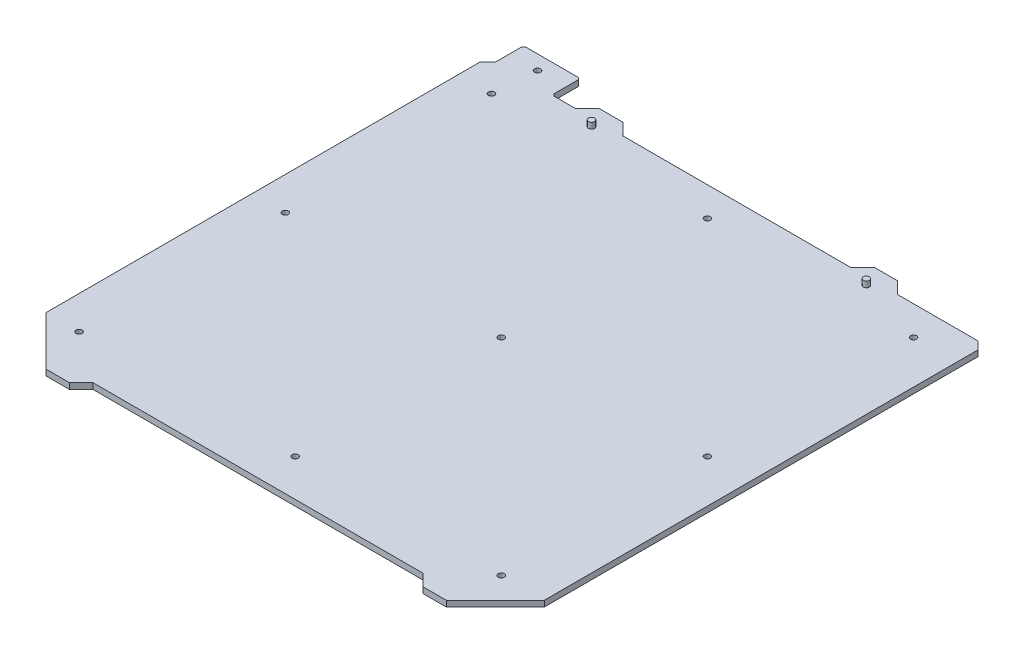
SolidWorks part; units mm, degrees
ref_plane "Front Plane" through (0, 0, 0) normal (0, 0, 1) x (1, 0, 0)
ref_plane "Top Plane" through (0, 0, 0) normal (0, 1, 0) x (1, 0, 0)
ref_plane "Right Plane" through (0, 0, 0) normal (1, 0, 0) x (0, 0, -1)
sketch "Sketch1" plane through (0, 0, 0) normal (0, 1, 0) x (1, 0, 0)
  line L0 (32.0022, 249.45) -> (32.0044, 249.45)
  line L1 (32.0044, 249.45) -> (32.0107, 249.448)
  line L2 (32.0107, 249.448) -> (32.0171, 249.447)
  line L3 (32.0171, 249.447) -> (32.019, 249.446)
  line L4 (32.019, 249.446) -> (32.0211, 249.445)
  line L5 (32.0211, 249.445) -> (32.0265, 249.442)
  line L6 (32.0265, 249.442) -> (32.0321, 249.438)
  line L7 (32.0321, 249.438) -> (32.0336, 249.437)
  line L8 (32.0336, 249.437) -> (32.0354, 249.435)
  line L9 (32.0354, 249.435) -> (33.0354, 248.435)
  line L10 (33.0354, 248.435) -> (33.0366, 248.434)
  line L11 (33.0366, 248.434) -> (33.0383, 248.432)
  line L12 (33.0383, 248.432) -> (33.0416, 248.426)
  line L13 (33.0416, 248.426) -> (33.0453, 248.421)
  line L14 (33.0453, 248.421) -> (33.0459, 248.419)
  line L15 (33.0459, 248.419) -> (33.047, 248.417)
  line L16 (33.047, 248.417) -> (33.0481, 248.411)
  line L17 (33.0481, 248.411) -> (33.0498, 248.404)
  line L18 (33.0498, 248.404) -> (33.0496, 248.402)
  line L19 (33.0496, 248.402) -> (33.05, 248.4)
  line L20 (33.05, 248.4) -> (33.05, 236.021)
  line L21 (33.05, 236.021) -> (33.9751, 235.096)
  line L22 (33.9751, 235.096) -> (34, 235.1)
  line L23 (34, 235.1) -> (45, 235.1)
  line L24 (45, 235.1) -> (45.0249, 235.096)
  line L25 (45.0249, 235.096) -> (50.9646, 241.035)
  line L26 (50.9646, 241.035) -> (50.9664, 241.037)
  line L27 (50.9664, 241.037) -> (50.9679, 241.038)
  line L28 (50.9679, 241.038) -> (50.9735, 241.042)
  line L29 (50.9735, 241.042) -> (50.9789, 241.045)
  line L30 (50.9789, 241.045) -> (50.981, 241.046)
  line L31 (50.981, 241.046) -> (50.9829, 241.047)
  line L32 (50.9829, 241.047) -> (50.9893, 241.048)
  line L33 (50.9893, 241.048) -> (50.9956, 241.05)
  line L34 (50.9956, 241.05) -> (50.9978, 241.05)
  line L35 (50.9978, 241.05) -> (51, 241.05)
  line L36 (51, 241.05) -> (63, 241.05)
  line L37 (63, 241.05) -> (63.0022, 241.05)
  line L38 (63.0022, 241.05) -> (63.0044, 241.05)
  line L39 (63.0044, 241.05) -> (63.0107, 241.048)
  line L40 (63.0107, 241.048) -> (63.0171, 241.047)
  line L41 (63.0171, 241.047) -> (63.019, 241.046)
  line L42 (63.019, 241.046) -> (63.0211, 241.045)
  line L43 (63.0211, 241.045) -> (63.0265, 241.042)
  line L44 (63.0265, 241.042) -> (63.0321, 241.038)
  line L45 (63.0321, 241.038) -> (63.0336, 241.037)
  line L46 (63.0336, 241.037) -> (63.0354, 241.035)
  line L47 (63.0354, 241.035) -> (68.9751, 235.096)
  line L48 (68.9751, 235.096) -> (69, 235.1)
  line L49 (69, 235.1) -> (185, 235.1)
  line L50 (185, 235.1) -> (185.025, 235.096)
  line L51 (185.025, 235.096) -> (190.965, 241.035)
  line L52 (190.965, 241.035) -> (190.966, 241.037)
  line L53 (190.966, 241.037) -> (190.968, 241.038)
  line L54 (190.968, 241.038) -> (190.974, 241.042)
  line L55 (190.974, 241.042) -> (190.979, 241.045)
  line L56 (190.979, 241.045) -> (190.981, 241.046)
  line L57 (190.981, 241.046) -> (190.983, 241.047)
  line L58 (190.983, 241.047) -> (190.989, 241.048)
  line L59 (190.989, 241.048) -> (190.996, 241.05)
  line L60 (190.996, 241.05) -> (190.998, 241.05)
  line L61 (190.998, 241.05) -> (191, 241.05)
  line L62 (191, 241.05) -> (203, 241.05)
  line L63 (203, 241.05) -> (203.002, 241.05)
  line L64 (203.002, 241.05) -> (203.004, 241.05)
  line L65 (203.004, 241.05) -> (203.011, 241.048)
  line L66 (203.011, 241.048) -> (203.017, 241.047)
  line L67 (203.017, 241.047) -> (203.019, 241.046)
  line L68 (203.019, 241.046) -> (203.021, 241.045)
  line L69 (203.021, 241.045) -> (203.026, 241.042)
  line L70 (203.026, 241.042) -> (203.032, 241.038)
  line L71 (203.032, 241.038) -> (203.034, 241.037)
  line L72 (203.034, 241.037) -> (203.035, 241.035)
  line L73 (203.035, 241.035) -> (208.975, 235.096)
  line L74 (208.975, 235.096) -> (209, 235.1)
  line L75 (209, 235.1) -> (250, 235.1)
  line L76 (250, 235.1) -> (250.004, 235.099)
  line L77 (250.004, 235.099) -> (250.009, 235.1)
  line L78 (250.009, 235.1) -> (250.021, 235.096)
  line L79 (250.021, 235.096) -> (250.034, 235.094)
  line L80 (250.034, 235.094) -> (250.038, 235.092)
  line L81 (250.038, 235.092) -> (250.042, 235.091)
  line L82 (250.042, 235.091) -> (250.053, 235.083)
  line L83 (250.053, 235.083) -> (250.064, 235.077)
  line L84 (250.064, 235.077) -> (250.067, 235.073)
  line L85 (250.067, 235.073) -> (250.071, 235.071)
  line L86 (250.071, 235.071) -> (254.071, 231.071)
  line L87 (254.071, 231.071) -> (254.073, 231.067)
  line L88 (254.073, 231.067) -> (254.077, 231.064)
  line L89 (254.077, 231.064) -> (254.083, 231.053)
  line L90 (254.083, 231.053) -> (254.091, 231.042)
  line L91 (254.091, 231.042) -> (254.092, 231.038)
  line L92 (254.092, 231.038) -> (254.094, 231.034)
  line L93 (254.094, 231.034) -> (254.096, 231.021)
  line L94 (254.096, 231.021) -> (254.1, 231.009)
  line L95 (254.1, 231.009) -> (254.099, 231.004)
  line L96 (254.099, 231.004) -> (254.1, 231)
  line L97 (254.1, 231) -> (254.1, 10)
  line L98 (254.1, 10) -> (254.099, 9.9957)
  line L99 (254.099, 9.9957) -> (254.1, 9.9913)
  line L100 (254.1, 9.9913) -> (254.096, 9.9787)
  line L101 (254.096, 9.9787) -> (254.094, 9.9658)
  line L102 (254.094, 9.9658) -> (254.092, 9.962)
  line L103 (254.092, 9.962) -> (254.091, 9.9577)
  line L104 (254.091, 9.9577) -> (254.083, 9.947)
  line L105 (254.083, 9.947) -> (254.077, 9.9357)
  line L106 (254.077, 9.9357) -> (254.073, 9.9329)
  line L107 (254.073, 9.9329) -> (254.071, 9.9293)
  line L108 (254.071, 9.9293) -> (229.071, -15.0707)
  line L109 (229.071, -15.0707) -> (229.067, -15.0732)
  line L110 (229.067, -15.0732) -> (229.064, -15.0766)
  line L111 (229.064, -15.0766) -> (229.053, -15.0831)
  line L112 (229.053, -15.0831) -> (229.042, -15.0906)
  line L113 (229.042, -15.0906) -> (229.038, -15.0918)
  line L114 (229.038, -15.0918) -> (229.034, -15.094)
  line L115 (229.034, -15.094) -> (229.021, -15.0962)
  line L116 (229.021, -15.0962) -> (229.009, -15.0996)
  line L117 (229.009, -15.0996) -> (229.004, -15.0992)
  line L118 (229.004, -15.0992) -> (229, -15.1)
  line L119 (229, -15.1) -> (217, -15.1)
  line L120 (217, -15.1) -> (216.996, -15.0992)
  line L121 (216.996, -15.0992) -> (216.991, -15.0996)
  line L122 (216.991, -15.0996) -> (216.979, -15.0962)
  line L123 (216.979, -15.0962) -> (216.966, -15.094)
  line L124 (216.966, -15.094) -> (216.962, -15.0918)
  line L125 (216.962, -15.0918) -> (216.958, -15.0906)
  line L126 (216.958, -15.0906) -> (216.947, -15.0831)
  line L127 (216.947, -15.0831) -> (216.936, -15.0766)
  line L128 (216.936, -15.0766) -> (216.933, -15.0732)
  line L129 (216.933, -15.0732) -> (216.929, -15.0707)
  line L130 (216.929, -15.0707) -> (210.959, -9.1)
  line L131 (210.959, -9.1) -> (43.0414, -9.1)
  line L132 (43.0414, -9.1) -> (37.0707, -15.0707)
  line L133 (37.0707, -15.0707) -> (37.0671, -15.0732)
  line L134 (37.0671, -15.0732) -> (37.0643, -15.0766)
  line L135 (37.0643, -15.0766) -> (37.053, -15.0831)
  line L136 (37.053, -15.0831) -> (37.0423, -15.0906)
  line L137 (37.0423, -15.0906) -> (37.038, -15.0918)
  line L138 (37.038, -15.0918) -> (37.0342, -15.094)
  line L139 (37.0342, -15.094) -> (37.0213, -15.0962)
  line L140 (37.0213, -15.0962) -> (37.0087, -15.0996)
  line L141 (37.0087, -15.0996) -> (37.0043, -15.0992)
  line L142 (37.0043, -15.0992) -> (37, -15.1)
  line L143 (37, -15.1) -> (25, -15.1)
  line L144 (25, -15.1) -> (24.9957, -15.0992)
  line L145 (24.9957, -15.0992) -> (24.9913, -15.0996)
  line L146 (24.9913, -15.0996) -> (24.9787, -15.0962)
  line L147 (24.9787, -15.0962) -> (24.9658, -15.094)
  line L148 (24.9658, -15.094) -> (24.962, -15.0918)
  line L149 (24.962, -15.0918) -> (24.9577, -15.0906)
  line L150 (24.9577, -15.0906) -> (24.947, -15.0831)
  line L151 (24.947, -15.0831) -> (24.9357, -15.0766)
  line L152 (24.9357, -15.0766) -> (24.9329, -15.0732)
  line L153 (24.9329, -15.0732) -> (24.9293, -15.0707)
  line L154 (24.9293, -15.0707) -> (-0.0707, 9.9293)
  line L155 (-0.0707, 9.9293) -> (-0.0732, 9.9329)
  line L156 (-0.0732, 9.9329) -> (-0.0766, 9.9357)
  line L157 (-0.0766, 9.9357) -> (-0.0831, 9.947)
  line L158 (-0.0831, 9.947) -> (-0.0906, 9.9577)
  line L159 (-0.0906, 9.9577) -> (-0.0918, 9.962)
  line L160 (-0.0918, 9.962) -> (-0.094, 9.9658)
  line L161 (-0.094, 9.9658) -> (-0.0962, 9.9787)
  line L162 (-0.0962, 9.9787) -> (-0.0996, 9.9913)
  line L163 (-0.0996, 9.9913) -> (-0.0992, 9.9957)
  line L164 (-0.0992, 9.9957) -> (-0.1, 10)
  line L165 (-0.1, 10) -> (-0.1, 231)
  line L166 (-0.1, 231) -> (-0.094, 231.034)
  line L167 (-0.094, 231.034) -> (-0.0766, 231.064)
  line L168 (-0.0766, 231.064) -> (-0.05, 231.087)
  line L169 (-0.05, 231.087) -> (-0.0174, 231.098)
  line L170 (-0.0174, 231.098) -> (0.0174, 231.098)
  line L171 (0.0174, 231.098) -> (0.025, 231.096)
  line L172 (0.025, 231.096) -> (3.95, 235.021)
  line L173 (3.95, 235.021) -> (3.95, 248.4)
  line L174 (3.95, 248.4) -> (3.9504, 248.402)
  line L175 (3.9504, 248.402) -> (3.9502, 248.404)
  line L176 (3.9502, 248.404) -> (3.9519, 248.411)
  line L177 (3.9519, 248.411) -> (3.953, 248.417)
  line L178 (3.953, 248.417) -> (3.9541, 248.419)
  line L179 (3.9541, 248.419) -> (3.9547, 248.421)
  line L180 (3.9547, 248.421) -> (3.9584, 248.426)
  line L181 (3.9584, 248.426) -> (3.9617, 248.432)
  line L182 (3.9617, 248.432) -> (3.9634, 248.434)
  line L183 (3.9634, 248.434) -> (3.9646, 248.435)
  line L184 (3.9646, 248.435) -> (4.9646, 249.435)
  line L185 (4.9646, 249.435) -> (4.9665, 249.437)
  line L186 (4.9665, 249.437) -> (4.9679, 249.438)
  line L187 (4.9679, 249.438) -> (4.9735, 249.442)
  line L188 (4.9735, 249.442) -> (4.9789, 249.445)
  line L189 (4.9789, 249.445) -> (4.981, 249.446)
  line L190 (4.981, 249.446) -> (4.9829, 249.447)
  line L191 (4.9829, 249.447) -> (4.9893, 249.448)
  line L192 (4.9893, 249.448) -> (4.9956, 249.45)
  line L193 (4.9956, 249.45) -> (4.9978, 249.45)
  line L194 (4.9978, 249.45) -> (5, 249.45)
  line L195 (5, 249.45) -> (32, 249.45)
  line L196 (32, 249.45) -> (32.0022, 249.45)
  line L197 (5.0207, 249.35) -> (4.05, 248.379)
  line L198 (4.05, 248.379) -> (4.05, 235)
  line L199 (4.05, 235) -> (4.0496, 234.998)
  line L200 (4.0496, 234.998) -> (4.0498, 234.996)
  line L201 (4.0498, 234.996) -> (4.0481, 234.989)
  line L202 (4.0481, 234.989) -> (4.047, 234.983)
  line L203 (4.047, 234.983) -> (4.0459, 234.981)
  line L204 (4.0459, 234.981) -> (4.0453, 234.979)
  line L205 (4.0453, 234.979) -> (4.0416, 234.974)
  line L206 (4.0416, 234.974) -> (4.0383, 234.968)
  line L207 (4.0383, 234.968) -> (4.0366, 234.966)
  line L208 (4.0366, 234.966) -> (4.0354, 234.965)
  line L209 (4.0354, 234.965) -> (0.0956, 231.025)
  line L210 (0.0956, 231.025) -> (0.1, 231)
  line L211 (0.1, 231) -> (0.1, 10.0414)
  line L212 (0.1, 10.0414) -> (25.0414, -14.9)
  line L213 (25.0414, -14.9) -> (36.9586, -14.9)
  line L214 (36.9586, -14.9) -> (42.9293, -8.9293)
  line L215 (42.9293, -8.9293) -> (42.9329, -8.9268)
  line L216 (42.9329, -8.9268) -> (42.9357, -8.9234)
  line L217 (42.9357, -8.9234) -> (42.947, -8.9169)
  line L218 (42.947, -8.9169) -> (42.9577, -8.9094)
  line L219 (42.9577, -8.9094) -> (42.962, -8.9082)
  line L220 (42.962, -8.9082) -> (42.9658, -8.906)
  line L221 (42.9658, -8.906) -> (42.9787, -8.9038)
  line L222 (42.9787, -8.9038) -> (42.9913, -8.9004)
  line L223 (42.9913, -8.9004) -> (42.9957, -8.9008)
  line L224 (42.9957, -8.9008) -> (43, -8.9)
  line L225 (43, -8.9) -> (211, -8.9)
  line L226 (211, -8.9) -> (211.004, -8.9008)
  line L227 (211.004, -8.9008) -> (211.009, -8.9004)
  line L228 (211.009, -8.9004) -> (211.021, -8.9038)
  line L229 (211.021, -8.9038) -> (211.034, -8.906)
  line L230 (211.034, -8.906) -> (211.038, -8.9082)
  line L231 (211.038, -8.9082) -> (211.042, -8.9094)
  line L232 (211.042, -8.9094) -> (211.053, -8.9169)
  line L233 (211.053, -8.9169) -> (211.064, -8.9234)
  line L234 (211.064, -8.9234) -> (211.067, -8.9268)
  line L235 (211.067, -8.9268) -> (211.071, -8.9293)
  line L236 (211.071, -8.9293) -> (217.041, -14.9)
  line L237 (217.041, -14.9) -> (228.959, -14.9)
  line L238 (228.959, -14.9) -> (253.9, 10.0414)
  line L239 (253.9, 10.0414) -> (253.9, 230.959)
  line L240 (253.9, 230.959) -> (249.959, 234.9)
  line L241 (249.959, 234.9) -> (209, 234.9)
  line L242 (209, 234.9) -> (208.966, 234.906)
  line L243 (208.966, 234.906) -> (208.936, 234.923)
  line L244 (208.936, 234.923) -> (208.913, 234.95)
  line L245 (208.913, 234.95) -> (208.902, 234.983)
  line L246 (208.902, 234.983) -> (208.902, 235.017)
  line L247 (208.902, 235.017) -> (208.904, 235.025)
  line L248 (208.904, 235.025) -> (202.979, 240.95)
  line L249 (202.979, 240.95) -> (191.021, 240.95)
  line L250 (191.021, 240.95) -> (185.096, 235.025)
  line L251 (185.096, 235.025) -> (185.098, 235.017)
  line L252 (185.098, 235.017) -> (185.098, 234.983)
  line L253 (185.098, 234.983) -> (185.087, 234.95)
  line L254 (185.087, 234.95) -> (185.064, 234.923)
  line L255 (185.064, 234.923) -> (185.034, 234.906)
  line L256 (185.034, 234.906) -> (185, 234.9)
  line L257 (185, 234.9) -> (69, 234.9)
  line L258 (69, 234.9) -> (68.9658, 234.906)
  line L259 (68.9658, 234.906) -> (68.9357, 234.923)
  line L260 (68.9357, 234.923) -> (68.9134, 234.95)
  line L261 (68.9134, 234.95) -> (68.9015, 234.983)
  line L262 (68.9015, 234.983) -> (68.9015, 235.017)
  line L263 (68.9015, 235.017) -> (68.9043, 235.025)
  line L264 (68.9043, 235.025) -> (62.9793, 240.95)
  line L265 (62.9793, 240.95) -> (51.0207, 240.95)
  line L266 (51.0207, 240.95) -> (45.0957, 235.025)
  line L267 (45.0957, 235.025) -> (45.0985, 235.017)
  line L268 (45.0985, 235.017) -> (45.0985, 234.983)
  line L269 (45.0985, 234.983) -> (45.0866, 234.95)
  line L270 (45.0866, 234.95) -> (45.0643, 234.923)
  line L271 (45.0643, 234.923) -> (45.0342, 234.906)
  line L272 (45.0342, 234.906) -> (45, 234.9)
  line L273 (45, 234.9) -> (34, 234.9)
  line L274 (34, 234.9) -> (33.9658, 234.906)
  line L275 (33.9658, 234.906) -> (33.9357, 234.923)
  line L276 (33.9357, 234.923) -> (33.9134, 234.95)
  line L277 (33.9134, 234.95) -> (33.9015, 234.983)
  line L278 (33.9015, 234.983) -> (33.9015, 235.017)
  line L279 (33.9015, 235.017) -> (33.9043, 235.025)
  line L280 (33.9043, 235.025) -> (32.9646, 235.965)
  line L281 (32.9646, 235.965) -> (32.9634, 235.966)
  line L282 (32.9634, 235.966) -> (32.9617, 235.968)
  line L283 (32.9617, 235.968) -> (32.9584, 235.974)
  line L284 (32.9584, 235.974) -> (32.9547, 235.979)
  line L285 (32.9547, 235.979) -> (32.9541, 235.981)
  line L286 (32.9541, 235.981) -> (32.953, 235.983)
  line L287 (32.953, 235.983) -> (32.9519, 235.989)
  line L288 (32.9519, 235.989) -> (32.9502, 235.996)
  line L289 (32.9502, 235.996) -> (32.9504, 235.998)
  line L290 (32.9504, 235.998) -> (32.95, 236)
  line L291 (32.95, 236) -> (32.95, 248.379)
  line L292 (32.95, 248.379) -> (31.9793, 249.35)
  line L293 (31.9793, 249.35) -> (5.0207, 249.35)
extrude "Boss-Extrude1" add sketch "Sketch1" along normal blind 3 contours L292 L293 L197 L198 L199 L200 L201 L202 L203 L204 L205 L206 L207 L208 L209 L210 L211 L212 L213 L214 L215 L216 L217 L218 L219 L220 L221 L222 L223 L224 L225 L226 L227 L228 L229 L230 L231 L232 L233 L234 L235 L236 L237 L238 L239 L240 L241 L242 L243 L244 L245
sketch "Sketch2" plane through (0, 3, 0) normal (0, 1, 0) x (1, 0, 0)
  line L0 (197, 231) -> (197, 240.95) construction
  line L1 (202.979, 240.95) -> (191.021, 240.95) construction
  line L2 (62.9793, 240.95) -> (51.0207, 240.95) construction
  line L3 (197, 240.95) -> (57, 240.95) construction
  line L4 (197, 240.95) -> (197, 231) construction
  line L5 (197, 231) -> (57, 231) construction
  line L6 (57, 240.95) -> (57, 231) construction
  line L7 (18.5, 242) -> (18.5, 249.35) construction
  line L8 (31.9793, 249.35) -> (5.0207, 249.35) construction
  line L9 (43, -8.9) -> (211, -8.9) construction
  line L10 (127, 10.0414) -> (127, -8.9) construction
  line L216 (127, 10.0414) -> (127, 234.9) construction
  line L217 (185, 234.9) -> (69, 234.9) construction
  line L218 (232, 10.0414) -> (232, 234.9) construction
  line L219 (249.959, 234.9) -> (209, 234.9) construction
  line L220 (17, 10.0414) -> (17, 234.9312) construction
  line L221 (232, 115.0414) -> (0.1, 115.0414) construction
  line L222 (0.1, 231) -> (0.1, 10.0414) construction
  line L223 (232, 220.0414) -> (0.1, 220.0414) construction
  line L224 (232, 10.0414) -> (0.1, 10.0414) construction
  circle A0 centre (17, 10.0414) radius 1.55
  circle A1 centre (127, 10.0414) radius 1.55
  circle A2 centre (232, 10.0414) radius 1.55
  circle A3 centre (232, 115.0414) radius 1.55
  circle A4 centre (232, 220.0414) radius 1.55
  circle A5 centre (127, 115.0414) radius 1.55
  circle A6 centre (17, 115.0414) radius 1.55
  circle A7 centre (17, 220.0414) radius 1.55
  circle A8 centre (127, 220.0414) radius 1.55
  circle A9 centre (197, 231) radius 1.55
  circle A10 centre (57, 231) radius 1.55
  circle A11 centre (18.5, 242) radius 1.55
  point P21 (57, 240.95)
  dimension "D1" = 3.1
  dimension "D2" = 3.1
  dimension "D3" = 3.1
  dimension "D4" = 3.1
  dimension "D5" = 3.1
  dimension "D6" = 3.1
  dimension "D11" = 3.1
  dimension "D12" = 3.1
  dimension "D13" = 3.1
  dimension "D15" = 3.1
  dimension "D16" = 3.1
  dimension "D18" = 3.1
  dimension "D7" = 110
  dimension "D8" = 105
  dimension "D9" = 105
  dimension "D10" = 105
  dimension "D14" = 9.95
  dimension "D17" = 7.35
extrude "Cut-Extrude1" cut sketch "Sketch2" against normal through all
sketch "Sketch3" plane through (0, 0, 0) normal (0, -1, 0) x (1, 0, 0)
  circle A0 centre (57, -231) radius 1.55 construction
  circle A1 centre (197, -231) radius 1.55 construction
  circle A2 centre (57, -231) radius 1.55
  circle A3 centre (197, -231) radius 1.55
extrude "Boss-Extrude3" add sketch "Sketch3" against normal blind 6
